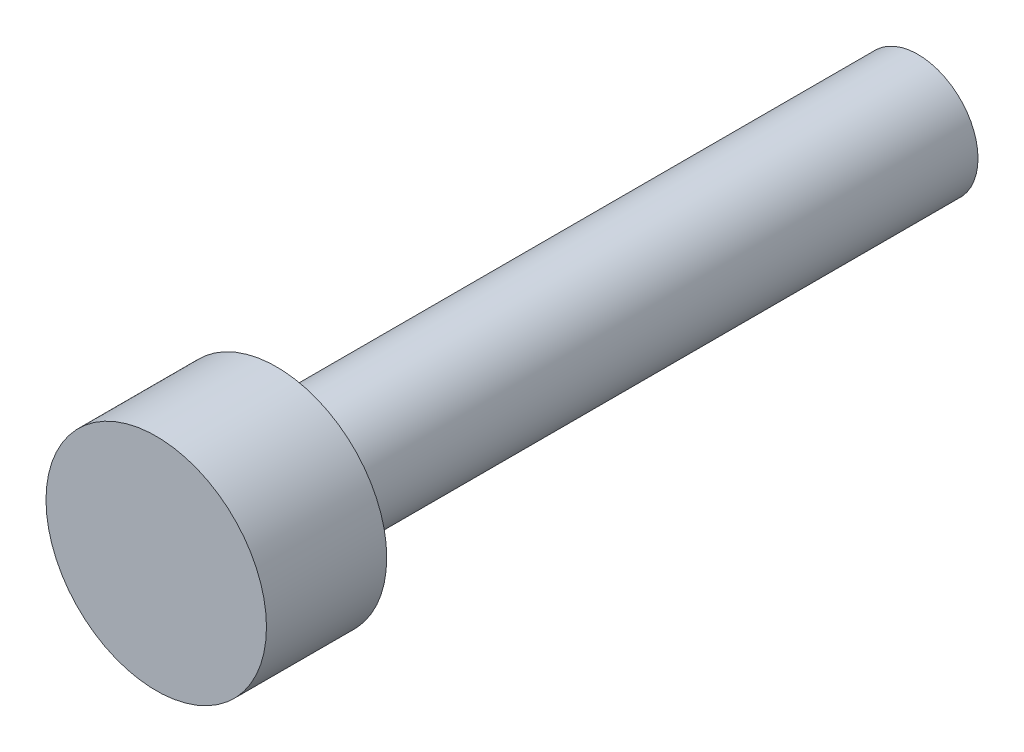
SolidWorks part; units mm, degrees
ref_plane "Front Plane" through (0, 0, 0) normal (0, 0, 1) x (1, 0, 0)
ref_plane "Top Plane" through (0, 0, 0) normal (0, 1, 0) x (1, 0, 0)
ref_plane "Right Plane" through (0, 0, 0) normal (1, 0, 0) x (0, 0, -1)
sketch "Shank_nominal_thread_envelope_profile" plane through (0, 0, 0) normal (0, 0, 1) x (1, 0, 0)
  circle A0 centre (0, 0) radius 1.5
  dimension "D1" = 3
extrude "Shank_nominal_thread_envelope" add sketch "Shank_nominal_thread_envelope_profile" along normal blind 16 from offset 16
sketch "Socket_head_envelope_profile" plane through (0, 0, 0) normal (0, 0, 1) x (1, 0, 0)
  circle A0 centre (0, 0) radius 2.75
  dimension "D1" = 5.5
extrude "Socket_head_envelope" add sketch "Socket_head_envelope_profile" along normal blind 3
